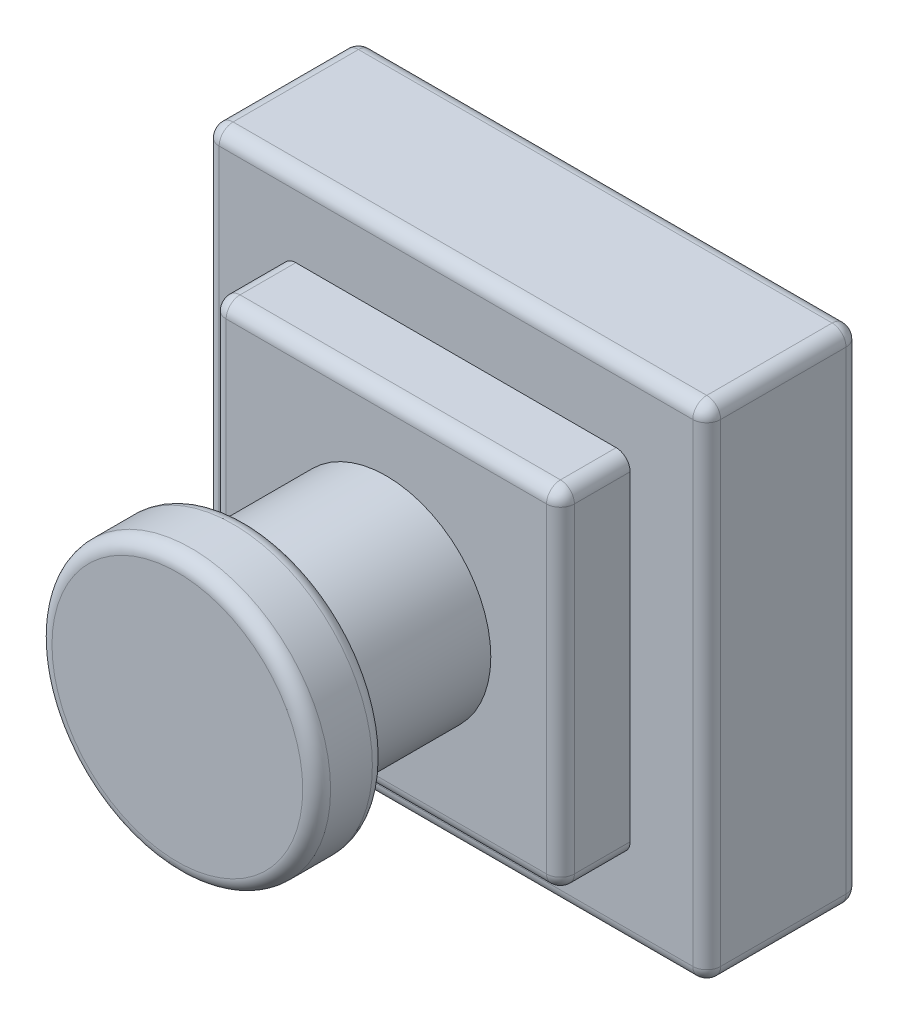
SolidWorks part; units mm, degrees
ref_plane "前视基准面" through (0, 0, 0) normal (0, 0, 1) x (1, 0, 0)
ref_plane "上视基准面" through (0, 0, 0) normal (0, 1, 0) x (1, 0, 0)
ref_plane "右视基准面" through (0, 0, 0) normal (1, 0, 0) x (0, 0, -1)
other "Configuration Table"
sketch "草图1" plane through (0, 0, 0) normal (0, 0, 1) x (1, 0, 0)
  line L1 (0, 0) -> (36, 0)
  line L2 (0, 0) -> (0, -36)
  line L3 (0, -36) -> (36, -36)
  line L4 (36, 0) -> (36, -36)
  dimension "D1" = 36
  dimension "D2" = 36
extrude "凸台-拉伸1" add sketch "草图1" along normal blind 11
fillet "圆角1" radius 1 12 edges at (36, -36, 5.5) (36, -18, 11) (36, 0, 5.5) (36, -18, 0) (0, -18, 11) (0, -18, 0) (18, -36, 0) (18, -36, 11) (18, 0, 0) (18, 0, 11) (0, -36, 5.5) (0, 0, 5.5)
sketch "草图2" plane through (0, 0, 11) normal (0, 0, 1) x (1, 0, 0)
  line L1 (5.5, -5.5) -> (30.5, -5.5)
  line L2 (5.5, -5.5) -> (5.5, -30.5)
  line L3 (5.5, -30.5) -> (30.5, -30.5)
  line L4 (30.5, -5.5) -> (30.5, -30.5)
  line L5 (36, -1) -> (36, -35) construction
  line L7 (1, 0) -> (35, 0) construction
  dimension "D1" = 25
  dimension "D2" = 25
  dimension "D3" = 5.5
  dimension "D4" = 5.5
extrude "凸台-拉伸2" add sketch "草图2" along normal blind 5
fillet "圆角2" radius 1 8 edges at (30.5, -30.5, 13.5) (18, -30.5, 16) (5.5, -30.5, 13.5) (5.5, -5.5, 13.5) (5.5, -18, 16) (30.5, -18, 16) (30.5, -5.5, 13.5) (18, -5.5, 16)
sketch "草图3" plane through (0, 0, 16) normal (0, 0, 1) x (1, 0, 0)
  line L0 (29.5, -5.5) -> (6.5, -5.5) construction
  line L1 (5.5, -6.5) -> (5.5, -29.5) construction
  circle A0 centre (18, -18) radius 7.5
  dimension "D1" = 15
  dimension "D2" = 12.5
  dimension "D3" = 12.5
extrude "凸台-拉伸3" add sketch "草图3" along normal blind 10
sketch "草图4" plane through (0, 0, 26) normal (0, 0, 1) x (1, 0, 0)
  circle A0 centre (18, -18) radius 10
  dimension "D1" = 20
extrude "凸台-拉伸4" add sketch "草图4" along normal blind 5
fillet "圆角3" radius 1 3 edges at (28, -18, 26) (25.5, -18, 26) (28, -18, 31)
